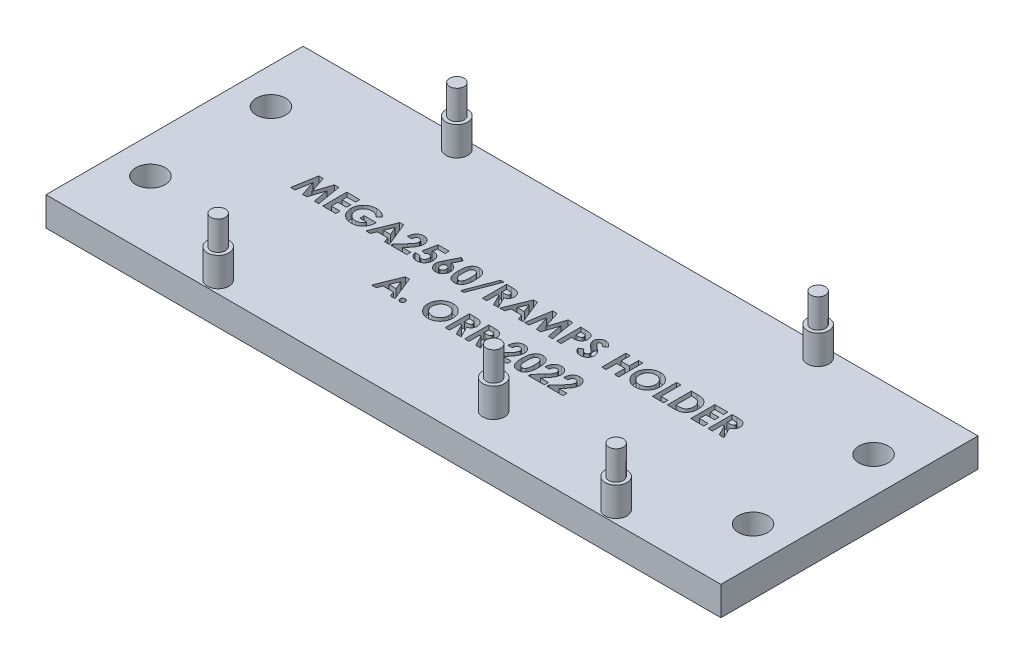
SolidWorks part; units mm, degrees
ref_plane "Front Plane" through (0, 0, 0) normal (0, 0, 1) x (1, 0, 0)
ref_plane "Top Plane" through (0, 0, 0) normal (0, 1, 0) x (1, 0, 0)
ref_plane "Right Plane" through (0, 0, 0) normal (1, 0, 0) x (0, 0, -1)
sketch "Sketch1" plane through (0, 0, 0) normal (0, 1, 0) x (1, 0, 0)
  line L0 (-29.6455, 13.3739) -> (-29.6455, -11.6261) construction
  line L1 (-37.1455, 27.5439) -> (102.8545, 27.5439)
  line L2 (-37.1455, 27.5439) -> (-37.1455, -25.7961)
  line L3 (-37.1455, -25.7961) -> (102.8545, -25.7961)
  line L4 (102.8545, 27.5439) -> (102.8545, -25.7961)
  line L5 (-29.6455, -11.6261) -> (95.3545, -11.6261) construction
  circle A0 centre (-29.6455, 13.3739) radius 3.05
  circle A1 centre (95.3545, 13.3739) radius 3.05
  circle A2 centre (95.3545, -11.6261) radius 3.05
  circle A3 centre (-29.6455, -11.6261) radius 3.05
  point P12 (-29.6455, 0.8739)
  point P13 (-37.1455, 0.8739)
  point P14 (32.8545, -11.6261)
  point P15 (32.8545, -25.7961)
  dimension "D3" = 6.1
  dimension "D1" = 53.34
  dimension "D2" = 140
  dimension "D4" = 25
  dimension "D5" = 125
extrude "Boss-Extrude1" add sketch "Sketch1" along normal blind 6
sketch "Sketch2" plane through (0, 6, 0) normal (0, 1, 0) x (1, 0, 0)
  line L0 (-17.9455, 27.5439) -> (-17.9455, -25.7961) construction
  line L1 (102.8545, 27.5439) -> (-37.1455, 27.5439) construction
  line L2 (-37.1455, -25.7961) -> (102.8545, -25.7961) construction
  line L3 (83.6545, 27.5439) -> (83.6545, -25.7961) construction
  line L4 (-17.9455, 0.8739) -> (83.6545, 0.8739) construction
  circle A0 centre (-2.7055, 25.0039) radius 2.25
  circle A1 centre (72.2245, 25.0039) radius 2.25
  circle A2 centre (48.0945, -18.1761) radius 2.25
  circle A3 centre (-3.9755, -23.2561) radius 2.25
  circle A4 centre (78.5745, -23.2561) radius 2.25
  point P10 (32.8545, 0.8739)
  point P11 (32.8545, 27.5439)
  point P22 (0, 0)
  point P23 (0, 0)
  point P24 (0, 0)
  point P25 (0, 0)
  dimension "D4" = 2.54
  dimension "D5" = 50.8
  dimension "D6" = 66.04
  dimension "D7" = 7.62
  dimension "D8" = 96.52
  dimension "D9" = 90.17
  dimension "D10" = 4.5
  dimension "D1" = 101.6
  dimension "D2" = 15.24
  dimension "D3" = 13.97
extrude "Boss-Extrude3" add sketch "Sketch2" along normal blind 6
sketch "Sketch3" plane through (0, 12, 0) normal (0, 1, 0) x (1, 0, 0)
  circle A0 centre (-2.7055, 25.0039) radius 1.5
  circle A1 centre (-3.9755, -23.2561) radius 1.5
  circle A2 centre (48.0945, -18.1761) radius 1.5
  circle A3 centre (78.5745, -23.2561) radius 1.5
  circle A4 centre (72.2245, 25.0039) radius 1.5
  dimension "D1" = 3
extrude "Boss-Extrude4" add sketch "Sketch3" along normal blind 6
sketch "Sketch4" plane through (0, 6, 0) normal (0, 1, 0) x (1, 0, 0)
  line L0 (-37.1455, 0.8739) -> (102.8545, 0.8739) construction
  line L1 (-37.1455, 27.5439) -> (-37.1455, -25.7961) construction
  line L2 (102.8545, -25.7961) -> (102.8545, 27.5439) construction
  text T0 "<b>MEGA2560/RAMPS HOLDER</b>\r\n<b>A. ORR 2022</b>" font "Century Gothic" height 5
extrude "Cut-Extrude1" cut sketch "Sketch4" against normal blind 2
